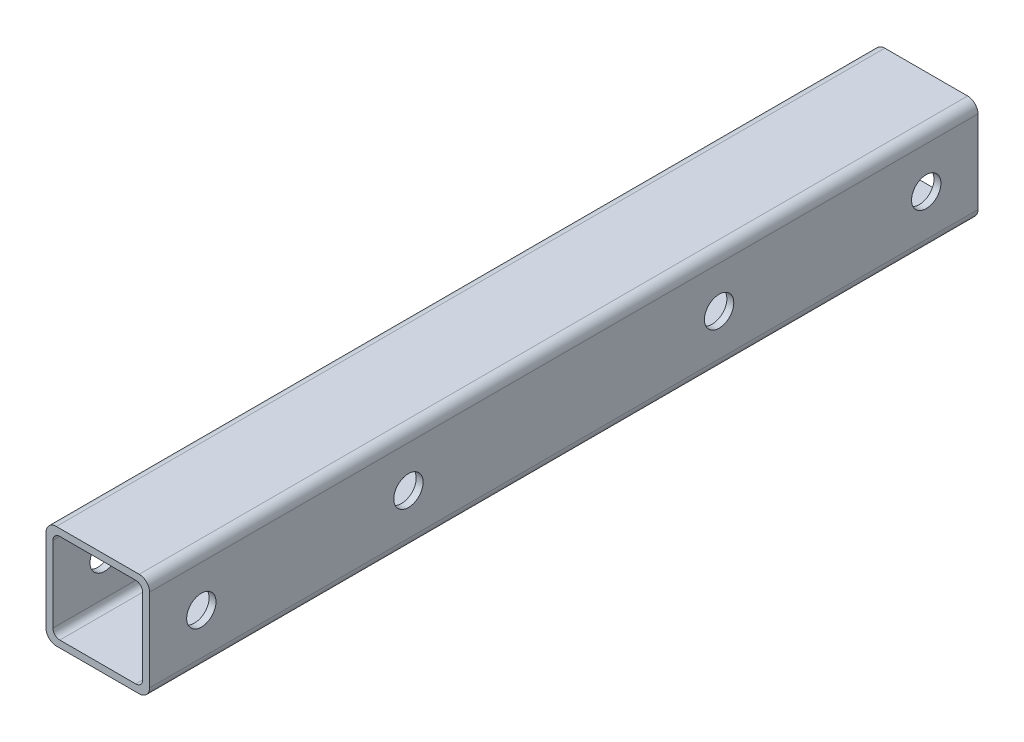
SolidWorks part; units mm, degrees
material "СТ3КП"
ref_plane "Спереди" through (0, 0, 0) normal (0, 0, 1) x (1, 0, 0)
ref_plane "Сверху" through (0, 0, 0) normal (0, 1, 0) x (1, 0, 0)
ref_plane "Справа" through (0, 0, 0) normal (1, 0, 0) x (0, 0, -1)
sketch "Эскиз1" plane through (0, 0, 0) normal (0, 0, 1) x (1, 0, 0)
  line L1 (-15, 0) -> (15, 0) construction
  line L2 (-15, 2000) -> (-15, 0) construction
  line B0 (-12, 30) -> (12, 30)
  line B1 (-15, 27) -> (-15, 3)
  line B2 (-12, 0) -> (12, 0)
  line B3 (15, 27) -> (15, 3)
  line B4 (-11, 28) -> (11, 28)
  line B5 (-13, 26) -> (-13, 4)
  line B6 (-11, 2) -> (11, 2)
  line B7 (13, 26) -> (13, 4)
  arc B8 (-15, 3) -> (-12, 0) centre (-12, 3) ccw
  arc B9 (12, 0) -> (15, 3) centre (12, 3) ccw
  arc B10 (12, 30) -> (15, 27) centre (12, 27) cw
  arc B11 (-12, 30) -> (-15, 27) centre (-12, 27) ccw
  arc B12 (-13, 4) -> (-11, 2) centre (-11, 4) ccw
  arc B13 (11, 2) -> (13, 4) centre (11, 4) ccw
  arc B14 (11, 28) -> (13, 26) centre (11, 26) cw
  arc B15 (-11, 28) -> (-13, 26) centre (-11, 26) ccw
sketch_block_instance "Блок-30х30х2-1"
sketch_block "Блок-30х30х2" parameters "D3"=3, "D4"=2, "D1"=30, "D2"=2
extrude "Бобышка-Вытянуть1" add sketch "Эскиз1" along normal up to surface (240 mm away)
sketch "Эскиз2" plane through (15, 0, 0) normal (1, 0, 0) x (0, 0, -1)
  line L0 (-240, 15) -> (-210, 15) construction
  line L1 (-240, 3) -> (-240, 27) construction
  line L2 (-210, 15) -> (-180, 15) construction
  line L3 (-180, 15) -> (-150, 15) construction
  line L4 (-150, 15) -> (-90, 15) construction
  line L5 (-90, 15) -> (-60, 15) construction
  line L6 (-60, 15) -> (-30, 15) construction
  line L7 (-30, 15) -> (0, 15) construction
  line L8 (0, 3) -> (0, 27) construction
  line L9 (-240, 30) -> (-240, 0) construction
  circle A0 centre (-225, 15) radius 4.25
  circle A1 centre (-165, 15) radius 4.25
  circle A2 centre (-75, 15) radius 4.25
  circle A3 centre (-15, 15) radius 4.25
  dimension "D1" = 8.5
extrude "Вырез-Вытянуть1" cut sketch "Эскиз2" against normal through all
